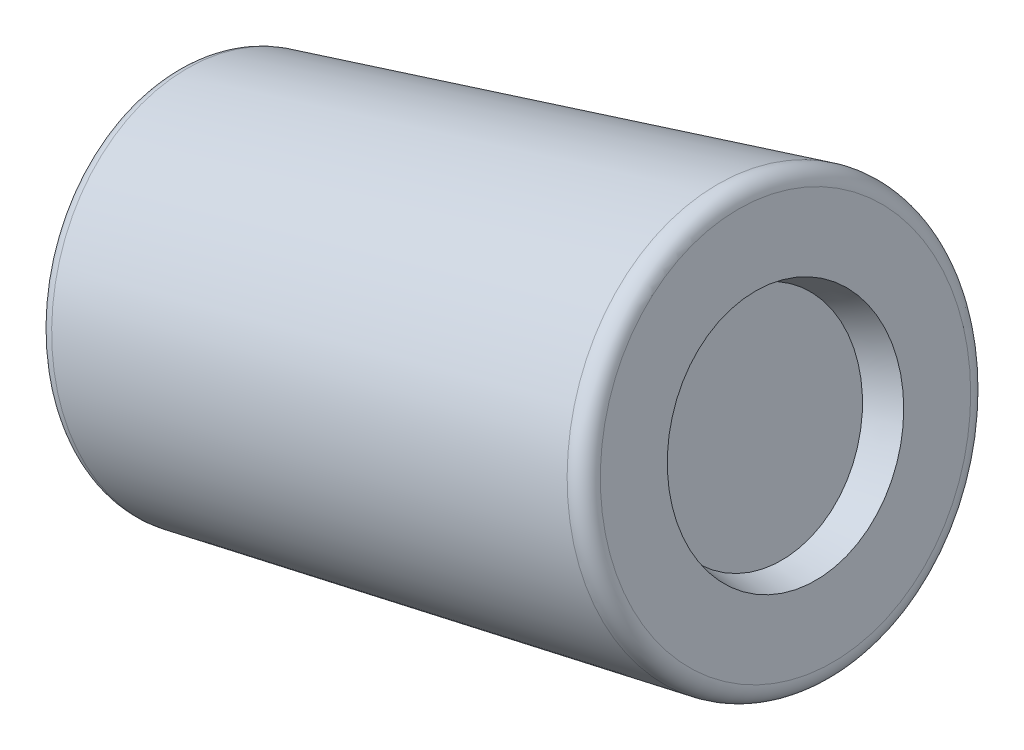
SolidWorks part; units mm, degrees
ref_plane "Plan1" through (0, 0, 0) normal (0, 0, 1) x (1, 0, 0)
ref_plane "Plan2" through (0, 0, 0) normal (0, 1, 0) x (1, 0, 0)
ref_plane "Plan3" through (0, 0, 0) normal (1, 0, 0) x (0, 0, -1)
sketch "Esquisse1" plane through (0, 0, 0) normal (0, 0, 1) x (1, 0, 0)
  line L0 (3.5556, 21.2559) -> (-89.1726, -4.0247) construction
  line L1 (-3.8948, 19.2247) -> (-12.5779, 16.8574)
  line L3 (-13.283, 19.4437) -> (-4.6839, 22.119)
  line L4 (-4.6839, 22.119) -> (-3.8948, 19.2247)
  line L5 (-13.283, 19.4437) -> (-12.5779, 16.8574)
  dimension "D2" = 2.032
  dimension "D5" = 3
  dimension "D6" = 9
revolve "Base-Révolution" add sketch "Esquisse1" angle 360 about L0
sketch "Esquisse3" plane through (1.2533, 0.3417, 0) normal (0.9648, 0.263, 0) x (0, 0, -1)
  circle A0 centre (0, 19.5722) radius 1.75
  circle A1 centre (0, 19.5722) radius 3 construction
  dimension "D1" = 3.5
extrude "Enlèv. mat.-Extru.1" cut sketch "Esquisse3" against normal blind 0.5 draft 16
fillet "Congé1" radius 0.25
